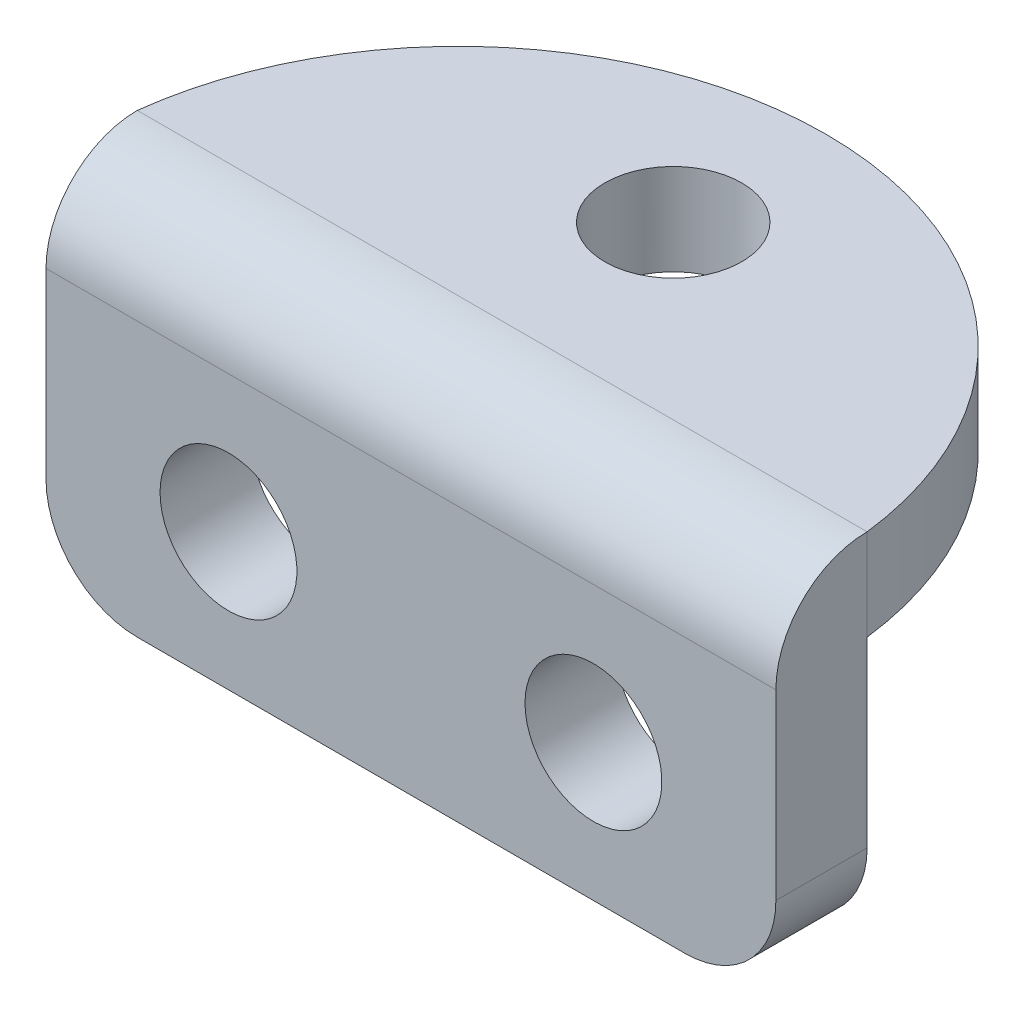
SolidWorks part; units mm, degrees
ref_plane "Front Plane" through (0, 0, 0) normal (0, 0, 1) x (1, 0, 0)
ref_plane "Top Plane" through (0, 0, 0) normal (0, 1, 0) x (1, 0, 0)
ref_plane "Right Plane" through (0, 0, 0) normal (1, 0, 0) x (0, 0, -1)
sketch "Sketch1" plane through (0, 0, 0) normal (0, 0, 1) x (1, 0, 0)
  line L0 (0, 0) -> (0, -4)
  line L1 (2, -6) -> (14, -6)
  line L2 (16, -4) -> (16, 0)
  line L3 (16, 0) -> (0, 0)
  arc A0 (0, -4) -> (2, -6) centre (2, -4) ccw
  arc A1 (16, -4) -> (14, -6) centre (14, -4) cw
  dimension "D1" = 4
  dimension "D4" = 2
  dimension "D2" = 12
  dimension "D3" = 16
  dimension "D5" = 4
extrude "Boss-Extrude1" add sketch "Sketch1" along normal blind 2
sketch "Sketch5" plane through (0, 0, 0) normal (0, 1, 0) x (1, 0, 0)
  line L0 (0, 0) -> (16, 0)
  arc A1 (0, 0) -> (16, 0) centre (8, -0.9598) cw
extrude "Boss-Extrude2" add sketch "Sketch5" along normal blind 2 separate body
sketch "Sketch9" plane through (0, 0, 0) normal (-1, 0, 0) x (0, 0, 1)
  line L0 (0, 2) -> (0, 0)
  line L1 (0, 0) -> (2, 0)
  arc A0 (2, 0) -> (0, 2) centre (0, 0) ccw
  dimension "D1" = 2
extrude "Boss-Extrude3" add sketch "Sketch9" against normal blind 16
sketch "Sketch10" plane through (0, 0, 0) normal (0, 0, -1) x (-1, 0, 0)
  line L0 (-16, -4) -> (-16, 2) construction
  line L1 (0, 2) -> (0, -4) construction
  line L2 (-2, -6) -> (-14, -6) construction
  circle A0 centre (-12, -3) radius 1.5
  circle A1 centre (-4, -3) radius 1.5
  dimension "D1" = 3
  dimension "D2" = 3
  dimension "D3" = 4
  dimension "D4" = 4
  dimension "D5" = 3
  dimension "D6" = 3
extrude "Cut-Extrude1" cut sketch "Sketch10" against normal through all
sketch "Sketch13" plane through (0, 2, 0) normal (0, 1, 0) x (1, 0, 0)
  line L0 (8, 3.75) -> (8, -2) construction
  line L2 (16, -2) -> (0, -2) construction
  circle A0 centre (8, 3.75) radius 1.5
  dimension "D1" = 5.75
extrude "Cut-Extrude2" cut sketch "Sketch13" against normal blind 4
